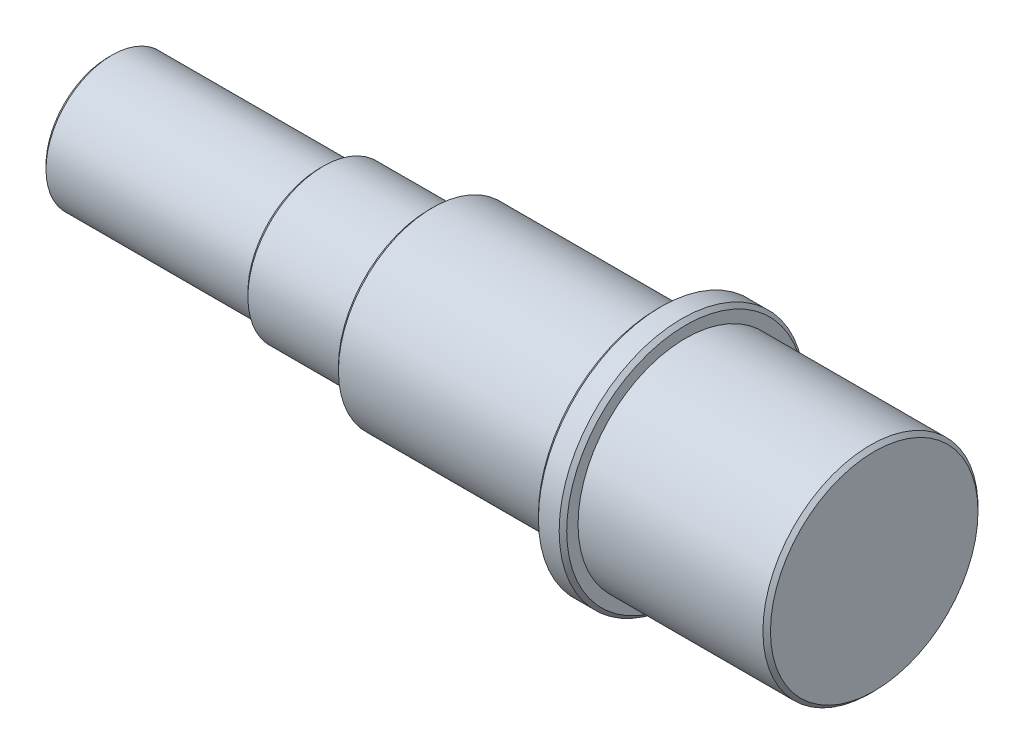
SolidWorks part; units mm, degrees
material "AISI 304"
ref_plane "Спереди" through (0, 0, 0) normal (0, 0, 1) x (1, 0, 0)
ref_plane "Сверху" through (0, 0, 0) normal (0, 1, 0) x (1, 0, 0)
ref_plane "Справа" through (0, 0, 0) normal (1, 0, 0) x (0, 0, -1)
sketch "Эскиз1" plane through (0, 0, 0) normal (0, 0, 1) x (1, 0, 0)
  line L0 (0, 0) -> (200.7585, 0) construction
  line L1 (0, 0) -> (0, 17.5)
  line L2 (56, 20) -> (85, 20)
  line L3 (85, 20) -> (85, 25)
  line L4 (85, 25) -> (145.5, 25)
  line L5 (145.5, 25) -> (145.5, 32.5)
  line L6 (145.5, 32.5) -> (153, 32.5)
  line L7 (153, 32.5) -> (153, 28.5)
  line L8 (153, 28.5) -> (203, 28.5)
  line L9 (203, 28.5) -> (203, 0)
  line L10 (203, 0) -> (0, 0)
  line L11 (56, 20) -> (56, 17.5)
  line L12 (56, 17.5) -> (0, 17.5)
  point P3 (149.25, 32.5)
  dimension "D1" = 57
  dimension "D2" = 50
  dimension "D3" = 7.5
  dimension "D4" = 40
  dimension "D5" = 50
  dimension "D6" = 65
  dimension "D7" = 118
  dimension "D8" = 147
  dimension "D9" = 35
  dimension "D10" = 203
revolve "Повернуть1" add sketch "Эскиз1" angle 360 about L0
chamfer "Фаска1" distance 1 angle 45 6 edges at (0, 0, 17.5) (56, 0, 20) (85, 0, 25) (145.5, 0, 32.5) (153, 0, 32.5) (203, 0, 28.5)
sketch "Эскиз2" plane through (0, 0, 0) normal (0, 0, 1) x (1, 0, 0)
  line L0 (7, 0) -> (47, 0) construction
  line L1 (7, 5) -> (47, 5)
  line L2 (7, -5) -> (47, -5)
  line L3 (0, 16.5) -> (0, -16.5) construction
  arc A0 (7, 5) -> (7, -5) centre (7, 0) ccw
  arc A1 (47, -5) -> (47, 5) centre (47, 0) ccw
  point P3 (27, 0)
  dimension "D3" = 7
  dimension "D2" = 50
  dimension "D1" = 10
extrude "Вырез-Вытянуть1" cut sketch "Эскиз2" along normal blind 5 from offset 17.5
